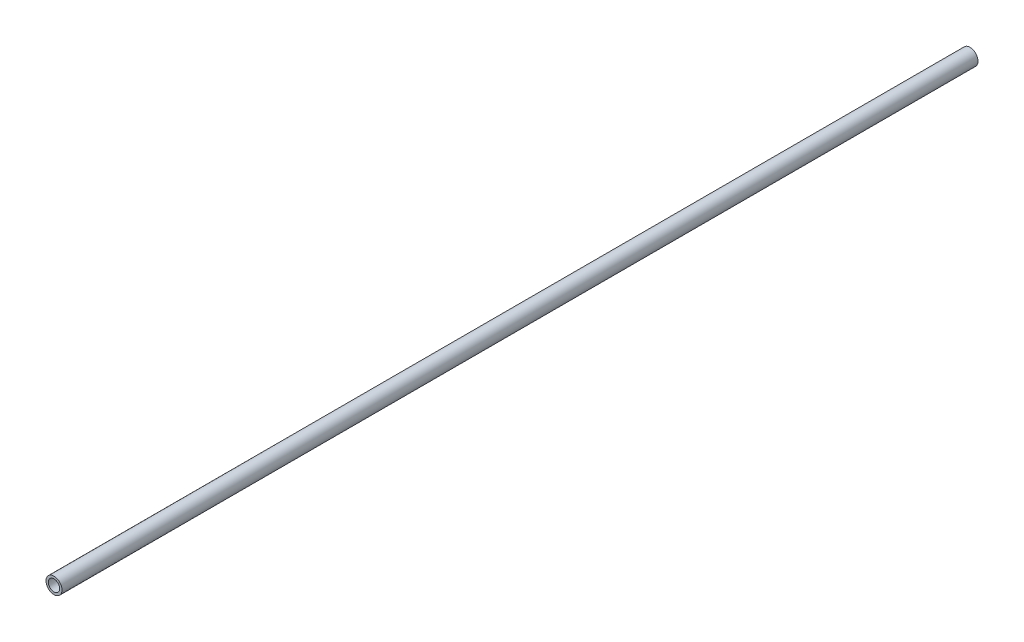
SolidWorks part; units mm, degrees
ref_plane "Front Plane" through (0, 0, 0) normal (0, 0, 1) x (1, 0, 0)
ref_plane "Top Plane" through (0, 0, 0) normal (0, 1, 0) x (1, 0, 0)
ref_plane "Right Plane" through (0, 0, 0) normal (1, 0, 0) x (0, 0, -1)
sketch "Sketch1" plane through (0, 0, 0) normal (0, 0, 1) x (1, 0, 0)
  circle A0 centre (0, 0) radius 13.335
  dimension "Pipe OD" = 26.67
extrude "Extrude-Thin1" add sketch "Sketch1" along normal mid plane 1524 thin thin type one direction reverse wall 3.9116
